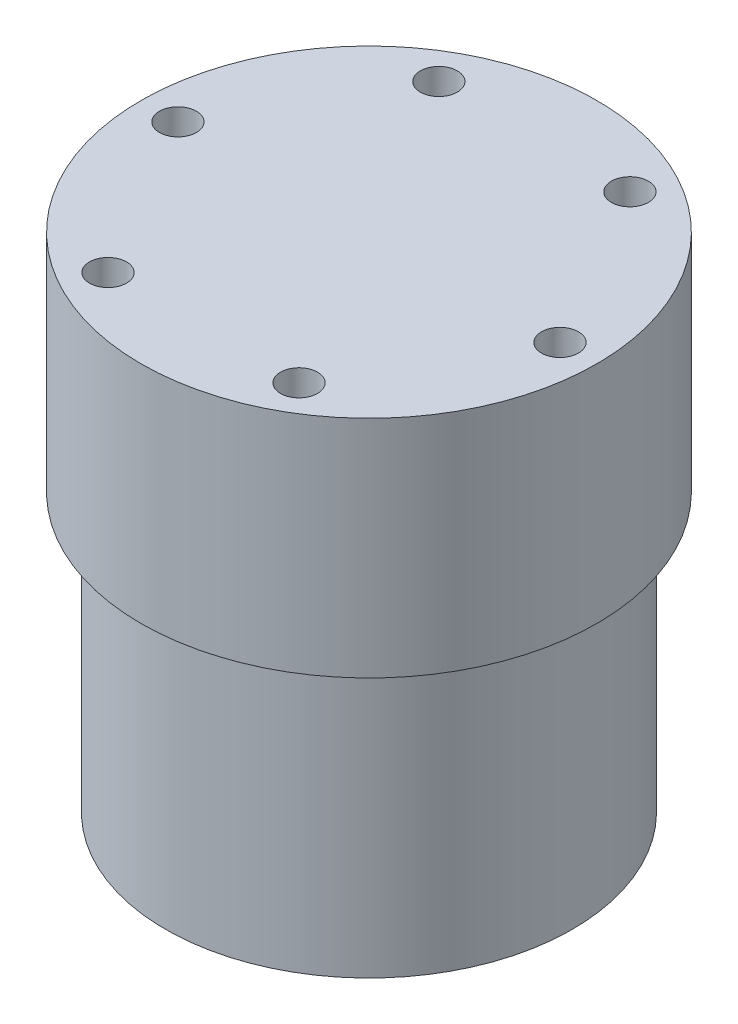
SolidWorks part; units mm, degrees
ref_plane "Front Plane" through (0, 0, 0) normal (0, 0, 1) x (1, 0, 0)
ref_plane "Top Plane" through (0, 0, 0) normal (0, 1, 0) x (1, 0, 0)
ref_plane "Right Plane" through (0, 0, 0) normal (1, 0, 0) x (0, 0, -1)
sketch "Sketch1" plane through (0, 0, 0) normal (0, 1, 0) x (1, 0, 0)
  circle A0 centre (0, 0) radius 16.5
  dimension "D1" = 33
extrude "Boss-Extrude1" add sketch "Sketch1" along normal blind 22.5
sketch "Sketch2" plane through (0, 22.5, 0) normal (0, 1, 0) x (1, 0, 0)
  circle A0 centre (0, 0) radius 18.5
  dimension "D1" = 37
extrude "Boss-Extrude2" add sketch "Sketch2" along normal blind 18.25
sketch "Sketch7" plane through (0, 40.75, 0) normal (0, 1, 0) x (1, 0, 0)
  line L0 (-18.5, 0) -> (18.5, 0) construction
  line L1 (0, -18.5) -> (0, 18.5) construction
  line L2 (0, 0) -> (9.25, 16.0215) construction
  circle A0 centre (0, 0) radius 18.5 construction
  circle A1 centre (15.5, 0) radius 1.5
  circle A2 centre (7.75, 13.4234) radius 1.5
  circle A3 centre (-15.5, 0) radius 1.5
  circle A4 centre (-7.75, 13.4234) radius 1.5
  circle A5 centre (7.75, -13.4234) radius 1.5
  circle A6 centre (-7.75, -13.4234) radius 1.5
  dimension "D1" = 3
  dimension "D3" = 3
  dimension "D2" = 30
  dimension "D4" = 31
  dimension "D5" = 31
extrude "Cut-Extrude2" cut sketch "Sketch7" against normal blind 6
